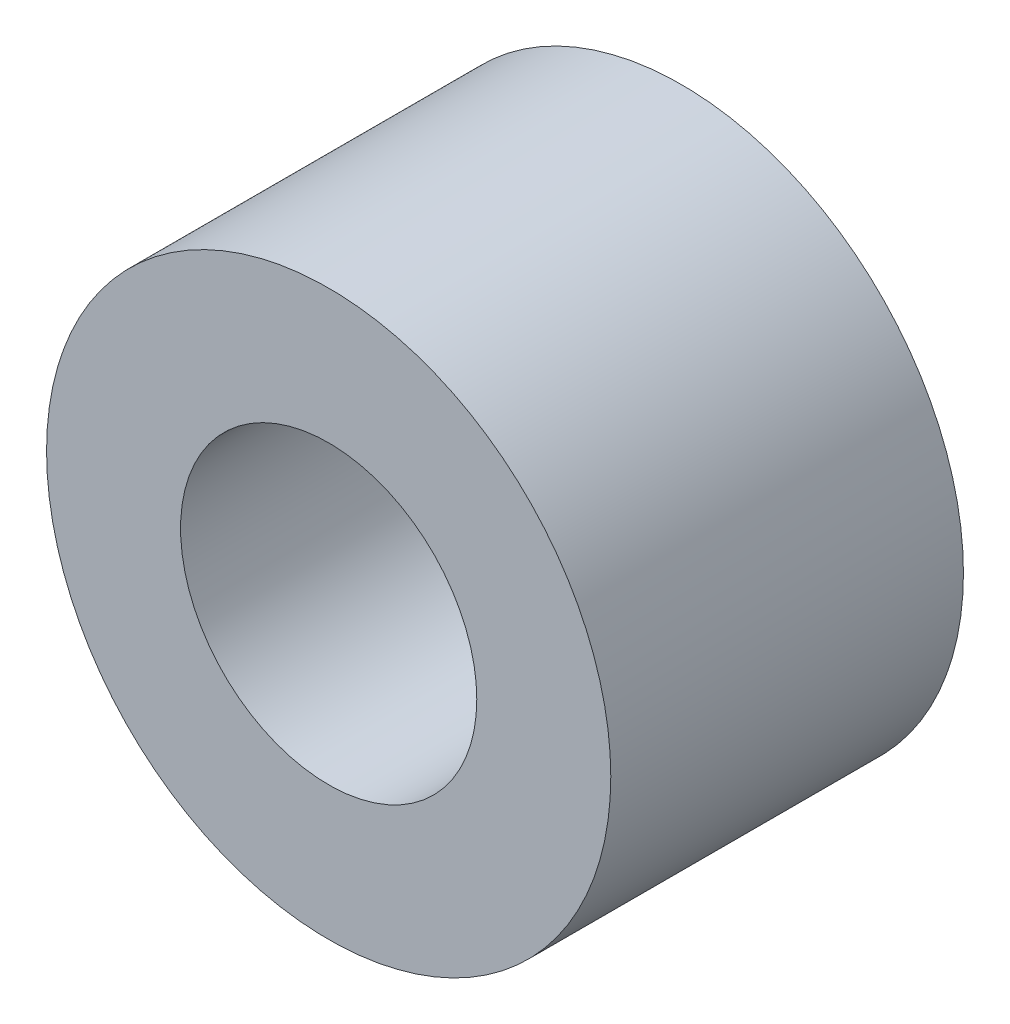
SolidWorks part; units mm, degrees
ref_plane "Front Plane" through (0, 0, 0) normal (0, 0, 1) x (1, 0, 0)
ref_plane "Top Plane" through (0, 0, 0) normal (0, 1, 0) x (1, 0, 0)
ref_plane "Right Plane" through (0, 0, 0) normal (1, 0, 0) x (0, 0, -1)
sketch "Sketch1" plane through (0, 0, 0) normal (0, 0, 1) x (1, 0, 0)
  line L3 (0, 0) -> (0, 4) construction
  circle A0 centre (0, 0) radius 2.1
  circle A1 centre (0, 0) radius 4
  dimension "D1" = 4.2
  dimension "D2" = 8
extrude "Boss-Extrude1" add sketch "Sketch1" along normal blind 5
